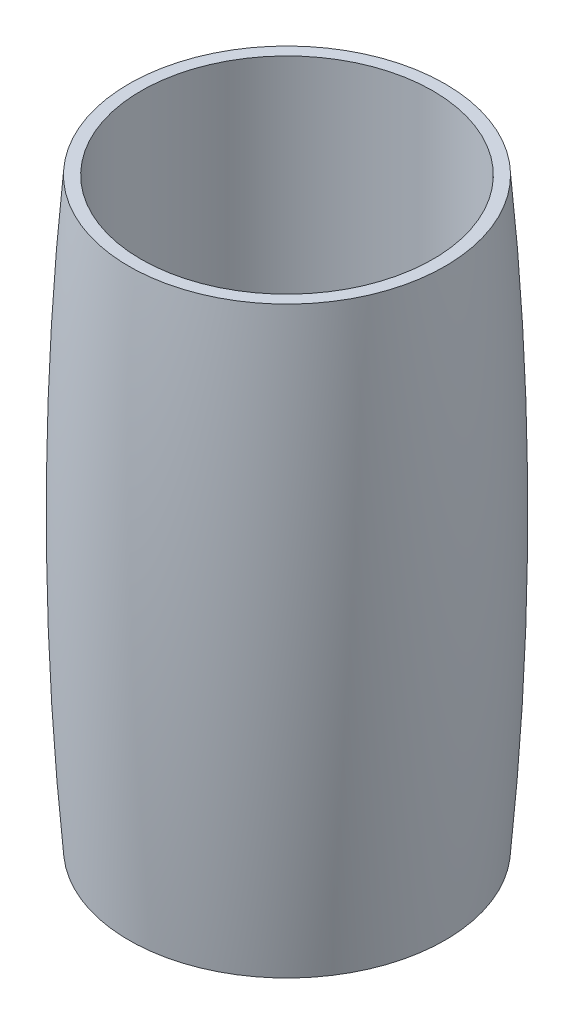
SolidWorks part; units mm, degrees
ref_plane "Front Plane" through (0, 0, 0) normal (0, 0, 1) x (1, 0, 0)
ref_plane "Top Plane" through (0, 0, 0) normal (0, 1, 0) x (1, 0, 0)
ref_plane "Right Plane" through (0, 0, 0) normal (1, 0, 0) x (0, 0, -1)
sketch "Sketch2" plane through (0, 0, 0) normal (0, 0, 1) x (1, 0, 0)
  line L0 (0, 0) -> (0, 152.4) construction
  line L1 (38.1, 152.4) -> (38.1, 0)
  line L2 (38.1, 152.4) -> (41.275, 152.4)
  line L3 (38.1, 0) -> (41.275, 0)
  arc A0 (41.275, 0) -> (41.275, 152.4) centre (-871.5375, 76.2) ccw
  point P7 (44.45, 76.2)
  dimension "D1" = 152.4
  dimension "D2" = 76.2
  dimension "D3" = 3.175
  dimension "D4" = 88.9
revolve "Revolve1" add sketch "Sketch2" angle 360 about L0
